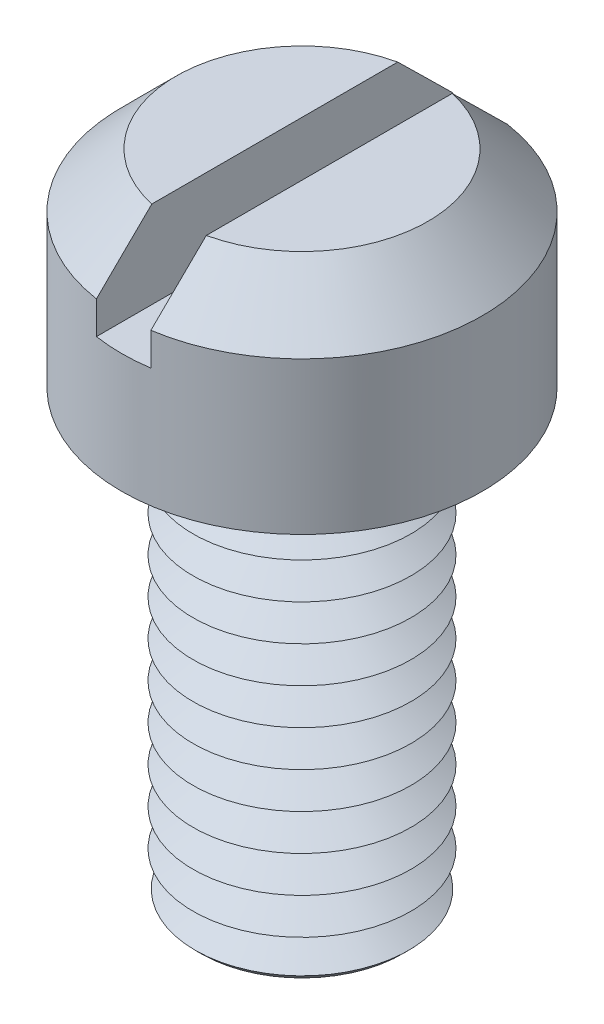
SolidWorks part; units mm, degrees
ref_plane "Front" through (0, 0, 0) normal (0, 0, 1) x (1, 0, 0)
ref_plane "Top" through (0, 0, 0) normal (0, 1, 0) x (1, 0, 0)
ref_plane "Right" through (0, 0, 0) normal (1, 0, 0) x (0, 0, -1)
ref_axis "Axis1" through (0, -50, 0) along (0, 1, 0)
sketch "Sketch ( driver )" plane through (0, 0, 0) normal (0, 0, 1) x (1, 0, 0)
  line L0 (0, 1.4448) -> (0.8809, 1.4448)
  line L1 (1.2619, 1.0638) -> (0.8809, 1.4448)
  line L2 (1.2619, 1.0638) -> (1.2619, 0)
  line L3 (1.2619, 0) -> (0.762, 0)
  line L4 (0.762, 0) -> (0.762, -3.0226)
  line L5 (0.762, -3.0226) -> (0.6096, -3.175)
  line L6 (0.6096, -3.175) -> (0, -3.175)
  line L7 (0, -3.175) -> (0, 1.4448)
  line L8 (0, 4.1777) -> (0, 1.4448) construction
  line L9 (0.762, 0.762) -> (0.762, 0.508) construction
  line L10 (0.762, 0.508) -> (0.542, 0.635) construction
  line L11 (0.542, 0.635) -> (0.762, 0.762) construction
  circle A0 centre (0, 1.4448) radius 0.1905 construction
  point P2 (0, 0.8352)
  point P12 (0.1905, 1.4448)
  dimension "D2" = 45
  dimension "Length" = 3.175
  dimension "D3" = 45
sketch "Sketch3" plane through (0, 0, 0) normal (0, 0, 1) x (1, 0, 0)
  line L8 (0, 0.8352) -> (0, -3.175)
  line L9 (0, -3.175) -> (0.6096, -3.175)
  line L10 (0.6096, -3.175) -> (0.762, -3.0226)
  line L11 (0.762, -3.0226) -> (0.762, 0.8352)
  line L12 (0.762, 0.8352) -> (0, 0.8352)
revolve "Shank Revolve ( driven )" add sketch "Sketch3" angle 360 about axis through (0, -50, 0) along (0, 1, 0)
sketch "Sketch4" plane through (0, 0, 0) normal (0, 0, 1) x (1, 0, 0)
  line L0 (0.542, 0.635) -> (0.762, 0.762)
  line L1 (0.762, 0.762) -> (1.27, 0.762)
  line L2 (1.27, 0.762) -> (1.27, -3.81)
  line L3 (0.542, 0.635) -> (0.762, 0.508)
  line L4 (0.762, 0.508) -> (0.542, 0.381)
  line L5 (0.542, 0.381) -> (0.762, 0.254)
  line L6 (0.762, 0) -> (0.762, -3.0226) construction
  line L7 (0.762, 0.254) -> (0.542, 0.127)
  line L8 (0.542, 0.127) -> (0.762, 0)
  line L9 (0.762, 0) -> (0.542, -0.127)
  line L10 (0.542, -0.127) -> (0.762, -0.254)
  line L11 (0.762, -0.254) -> (0.542, -0.381)
  line L12 (0.542, -0.381) -> (0.762, -0.508)
  line L13 (0.762, -0.508) -> (0.542, -0.635)
  line L14 (0.542, -0.635) -> (0.762, -0.762)
  line L15 (0.762, -0.762) -> (0.542, -0.889)
  line L16 (0.542, -0.889) -> (0.762, -1.016)
  line L17 (0.762, -1.016) -> (0.542, -1.143)
  line L18 (0.542, -1.143) -> (0.762, -1.27)
  line L19 (0.762, -1.27) -> (0.542, -1.397)
  line L20 (0.542, -1.397) -> (0.762, -1.524)
  line L21 (0.762, -1.524) -> (0.542, -1.651)
  line L22 (0.542, -1.651) -> (0.762, -1.778)
  line L23 (0.762, -1.778) -> (0.542, -1.905)
  line L24 (0.542, -1.905) -> (0.762, -2.032)
  line L25 (0.762, -2.032) -> (0.542, -2.159)
  line L26 (0.542, -2.159) -> (0.762, -2.286)
  line L27 (0.762, -2.286) -> (0.542, -2.413)
  line L28 (0.542, -2.413) -> (0.762, -2.54)
  line L29 (0.762, -2.54) -> (0.542, -2.667)
  line L30 (0.542, -2.667) -> (0.762, -2.794)
  line L31 (0.762, -2.794) -> (0.542, -2.921)
  line L32 (0.542, -2.921) -> (0.762, -3.048)
  line L33 (0.762, -3.048) -> (0.542, -3.175)
  line L34 (0.542, -3.175) -> (0.762, -3.302)
  line L35 (0.762, -3.302) -> (0.542, -3.429)
  line L36 (0.542, -3.429) -> (0.762, -3.556)
  line L37 (0.762, -3.556) -> (0.542, -3.683)
  line L38 (0.542, -3.683) -> (0.762, -3.81)
  line L39 (0.762, -3.81) -> (1.27, -3.81)
  dimension "D1" = 0.508
revolve "Thread Revolve Cut ( driven )" cut sketch "Sketch4" angle 360 about axis through (0, -50, 0) along (0, 1, 0)
sketch "Sketch5" plane through (0, 0, 0) normal (0, 0, 1) x (1, 0, 0)
  line L0 (0, 1.4448) -> (0, 0)
  line L1 (0, 0) -> (1.2619, 0)
  line L2 (1.2619, 0) -> (1.2619, 1.0638)
  line L3 (1.2619, 1.0638) -> (0.8809, 1.4448)
  line L4 (0.8809, 1.4448) -> (0, 1.4448)
revolve "Head Revolve ( driven )" add sketch "Sketch5" angle 360 about axis through (0, -50, 0) along (0, 1, 0)
sketch "Sketch2" plane through (0, 1.4448, 0) normal (0, 1, 0) x (-1, 0, 0)
  line L1 (0.1905, -16.0765) -> (-0.1905, -16.0765)
  line L2 (0.1905, -16.0765) -> (0.1905, 16.0765)
  line L3 (0.1905, 16.0765) -> (-0.1905, 16.0765)
  line L4 (-0.1905, -16.0765) -> (-0.1905, 16.0765)
  point P4 (-0.1905, 0)
  point P5 (0, -16.0765)
extrude "Hex Cut ( driven )" cut sketch "Sketch2" against normal up to vertex (0.6096 mm away) up to point (0, 0.8352, 0)
equation "\"Thick@Sketch ( driver )\" = 0.948*\"Diam@Sketch ( driver )\""
equation "\"D1@Sketch ( driver )\" = .25 * \"Diam@Sketch ( driver )\""
equation "\"Pitch@Sketch ( driver )\" =  \"Diam@Sketch ( driver )\"/6"
equation "\"D4@Sketch ( driver )\" = .4*\"Diam@Sketch ( driver )\""
equation "\"End Chamfer@Sketch ( driver )\" = .1*\"Diam@Sketch ( driver )\""
equation "\"D5@Sketch ( driver )\" = .25 * \"Diam@Sketch ( driver )\""
equation "\"Threaded@Sketch ( driver )\" = 2.5*\"Diam@Sketch ( driver )\""
equation "\"Head Dia@Sketch ( driver )\" = 1.656 * \"Diam@Sketch ( driver )\""
